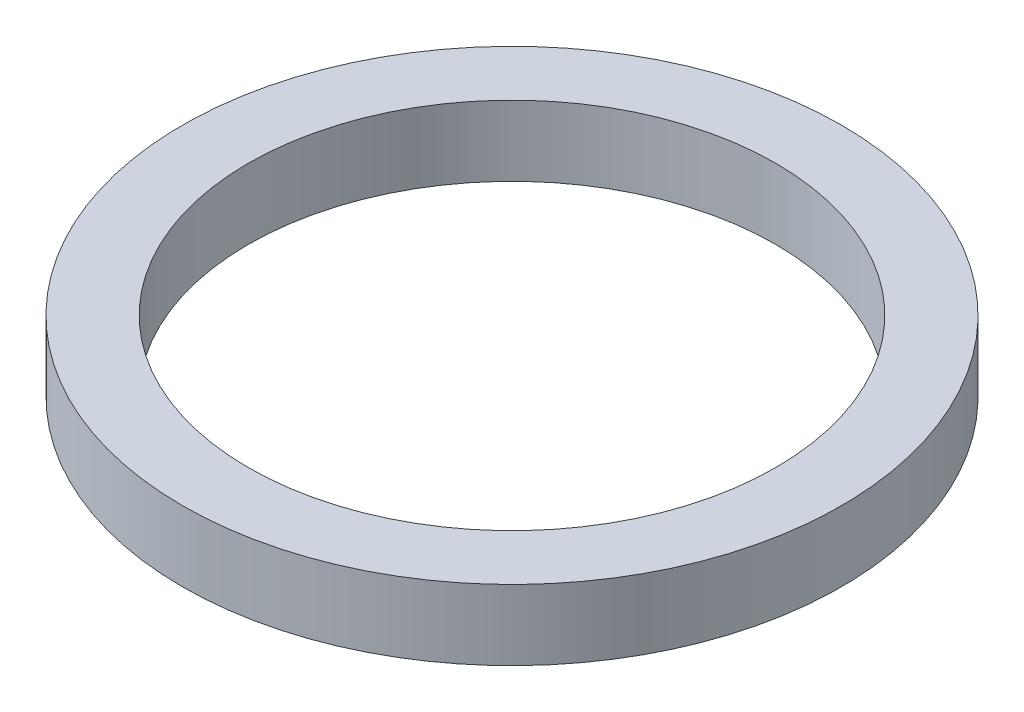
SolidWorks part; units mm, degrees
material "ASTM A36 Steel"
ref_plane "Front Plane" through (0, 0, 0) normal (0, 0, 1) x (1, 0, 0)
ref_plane "Top Plane" through (0, 0, 0) normal (0, 1, 0) x (1, 0, 0)
ref_plane "Right Plane" through (0, 0, 0) normal (1, 0, 0) x (0, 0, -1)
sketch "Sketch1" plane through (0, 0, 0) normal (0, 1, 0) x (1, 0, 0)
  circle A0 centre (0, 0) radius 60
  circle A1 centre (0, 0) radius 75
  dimension "D1" = 120
  dimension "D2" = 150
extrude "Boss-Extrude1" add sketch "Sketch1" along normal blind 16
